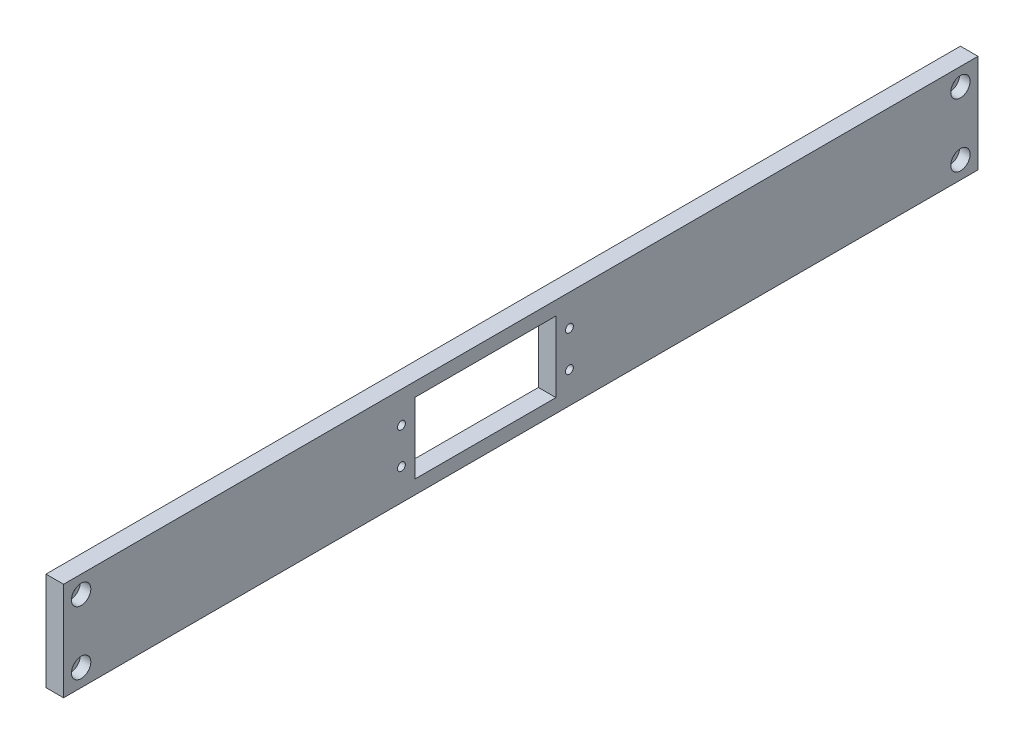
SolidWorks part; units mm, degrees
ref_plane "Front Plane" through (0, 0, 0) normal (0, 0, 1) x (1, 0, 0)
ref_plane "Top Plane" through (0, 0, 0) normal (0, 1, 0) x (1, 0, 0)
ref_plane "Right Plane" through (0, 0, 0) normal (1, 0, 0) x (0, 0, -1)
sketch "Sketch1" plane through (0, 0, 0) normal (0, 1, 0) x (1, 0, 0)
  line L1 (-2.5, 130.1) -> (2.5, 130.1)
  line L2 (-2.5, 130.1) -> (-2.5, -130.1)
  line L3 (-2.5, -130.1) -> (2.5, -130.1)
  line L4 (2.5, 130.1) -> (2.5, -130.1)
  line L5 (-2.5, 130.1) -> (2.5, -130.1) construction
  line L6 (-2.5, -130.1) -> (2.5, 130.1) construction
  point P0 (0, 0)
  dimension "D1" = 260.2
  dimension "D2" = 5
extrude "Boss-Extrude1" add sketch "Sketch1" along normal blind 28
sketch "Sketch2" plane through (2.5, 0, 0) normal (1, 0, 0) x (0, 0, -1)
  line L0 (-130.1, 28) -> (-130.1, 0) construction
  line L1 (-30.12, 24.06) -> (10, 24.06)
  line L2 (-30.12, 24.06) -> (-30.12, 3.94)
  line L3 (-30.12, 3.94) -> (10, 3.94)
  line L4 (10, 24.06) -> (10, 3.94)
  line L5 (-30.12, 24.06) -> (10, 3.94) construction
  line L6 (-30.12, 3.94) -> (10, 24.06) construction
  point P0 (-10.06, 14)
  point P9 (-130.1, 14)
  dimension "D1" = 40.12
  dimension "D2" = 20.12
  dimension "D3" = 10
extrude "Cut-Extrude1" cut sketch "Sketch2" against normal through all
sketch "Sketch3" plane through (2.5, 0, 0) normal (1, 0, 0) x (0, 0, -1)
  line L0 (-30.12, 24.06) -> (-30.12, 3.94) construction
  line L1 (10, 24.06) -> (-30.12, 24.06) construction
  circle A0 centre (-33.96, 19.1) radius 1.125
  circle A1 centre (-33.96, 8.9) radius 1.125
  circle A2 centre (13.84, 19.1) radius 1.125
  circle A3 centre (13.84, 8.9) radius 1.125
  point P15 (-30.12, 14)
  point P18 (-10.06, 24.06)
  dimension "D1" = 2.25
  dimension "D2" = 5.1
  dimension "D3" = 23.9
  dimension "D4" = 10.2
  dimension "D5" = 23.9
extrude "Cut-Extrude2" cut sketch "Sketch3" against normal through all
sketch "Sketch4" plane through (2.5, 0, 0) normal (1, 0, 0) x (0, 0, -1)
  line L0 (-130.1, 28) -> (130.1, 28) construction
  line L1 (-130.1, 28) -> (-130.1, 0) construction
  circle A0 centre (-125.1, 23) radius 2.75
  dimension "D1" = 5.5
  dimension "D2" = 5
  dimension "D3" = 5
extrude "Cut-Extrude3" cut sketch "Sketch4" against normal blind 3
sketch "Sketch5" plane through (-0.5, 0, 0) normal (1, 0, 0) x (0, 0, -1)
  circle A0 centre (-125.1, 23) radius 1.55
  circle A1 centre (-125.1, 23) radius 2.75 construction
  dimension "D1" = 3.1
extrude "Cut-Extrude4" cut sketch "Sketch5" against normal through all
ref_plane "Plane1" through (0, 14, 0) normal (0, 1, 0) x (1, 0, 0)
mirror "Mirror2" about plane through (0, 0, 0) normal (0, 0, 1) of "Cut-Extrude3", "Cut-Extrude4" second plane through (0, 14, 0) second plane normal (0, 1, 0)
